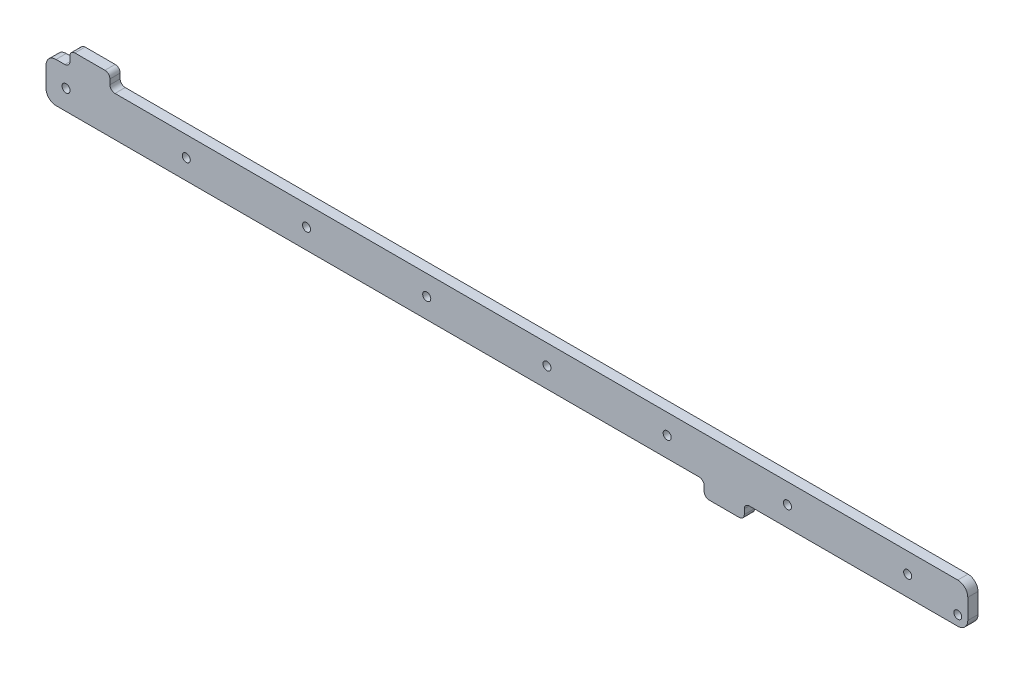
SolidWorks part; units mm, degrees
material "PC High Viscosity"
ref_plane "Front Plane" through (0, 0, 0) normal (0, 0, 1) x (1, 0, 0)
ref_plane "Top Plane" through (0, 0, 0) normal (0, 1, 0) x (1, 0, 0)
ref_plane "Right Plane" through (0, 0, 0) normal (1, 0, 0) x (0, 0, -1)
sketch "Sketch1" plane through (0, 0, 0) normal (0, 0, 1) x (1, 0, 0)
  line L1 (0, 0) -> (40.5308, 0)
  line L2 (0, 0) -> (0, 25.4)
  line L3 (0, 25.4) -> (15.1308, 25.4)
  line L4 (584.2, 0) -> (584.2, 25.4)
  line L5 (15.1308, 34.925) -> (40.5308, 34.925)
  line L6 (40.5308, 34.925) -> (40.5308, 25.4)
  line L7 (15.1308, 34.925) -> (15.1308, 25.4)
  line L11 (584.2, 10.0162) -> (577.85, 13.6823) construction
  line L12 (577.85, 13.6823) -> (571.5, 10.0162) construction
  line L13 (571.5, 10.0162) -> (571.5, 2.6838) construction
  line L14 (571.5, 2.6838) -> (577.85, -0.9823) construction
  line L15 (577.85, -0.9823) -> (584.2, 2.6838) construction
  line L16 (584.2, 2.6838) -> (584.2, 10.0162) construction
  line L19 (417.1409, 0) -> (417.1409, -9.525)
  line L20 (417.1409, -9.525) -> (442.5409, -9.525)
  line L21 (442.5409, -9.525) -> (442.5409, 0)
  line L22 (40.5308, 25.4) -> (584.2, 25.4)
  line L23 (40.5308, 0) -> (417.1409, 0)
  line L24 (442.5409, 0) -> (584.2, 0)
  circle A0 centre (577.85, 6.35) radius 2.4892
  circle A1 centre (577.85, 6.35) radius 6.35 construction
  point P24 (417.1409, -4.7625)
  dimension "D5" = 4.9784
  dimension "D6" = 9.525
  dimension "D7" = 12.7
  dimension "D1" = 584.2
  dimension "D2" = 25.4
  dimension "D3" = 25.4
  dimension "D4" = 167.0591
  dimension "D8" = 40.5308
  dimension "D9" = 25.4
extrude "Boss-Extrude1" add sketch "Sketch1" along normal blind 6.477
fillet "Fillet2" radius 6.35 4 edges at (0, 0, 3.2385) (0, 25.4, 3.2385) (584.2, 25.4, 3.2385) (584.2, 0, 3.2385)
sketch "Sketch2" plane through (0, 0, 6.477) normal (0, 0, 1) x (1, 0, 0)
  line L0 (6.35, 25.4) -> (15.1308, 25.4) construction
  line L1 (584.2, 19.05) -> (584.2, 6.35) construction
  circle A0 centre (546.1, 12.7) radius 2.0193
  dimension "D1" = 4.0386
  dimension "D2" = 12.7
  dimension "D3" = 38.1
hole_wizard "CSK for #10 Flat Head Machine Screw (100)1" positions "Sketch4" profile "Sketch5" countersink size "#10" standard "ANSI Inch" end condition through all
sketch "Sketch4" plane through (0, 0, 6.477) normal (0, 0, 1) x (1, 0, 0)
  line L0 (584.2, 12.7) -> (0, 12.7) construction
  line L1 (584.2, 19.05) -> (584.2, 6.35) construction
  line L2 (0, 6.35) -> (0, 19.05) construction
  line L3 (6.35, 25.4) -> (15.1308, 25.4) construction
  point P11 (546.1, 12.7)
  dimension "D1" = 12.7
  dimension "D2" = 38.1
sketch "Sketch5" plane through (546.1, 12.7, 6.477) normal (1, 0, 0) x (0, -1, 0)
  line L0 (0, 0) -> (0, 6.477)
  line L1 (0, 6.477) -> (2.5527, 6.477)
  line L2 (2.5527, 6.477) -> (2.5527, 1.9608)
  line L3 (2.5527, 1.9608) -> (4.8895, 0)
  line L5 (4.8895, 0) -> (0, 0)
  line L6 (-2.5527, 1.9608) -> (-4.8895, 0) construction
  line L11 (0, -6.35) -> (0, 107.95) construction
  dimension "Thru Hole Dia." = 5.1054
  dimension "Thru Hole Depth" = 6.477
  dimension "Near C'Sink Dia." = 9.779
  dimension "Near C'Sink Angle" = 100
pattern_linear "LPattern1" count 8 spacing 76.2 along (-1, 0, 0) of "CSK for #10 Flat Head Machine Screw (100)1"
mirror "Mirror2" about plane through (0, 0, 0) normal (0, 0, 1) of bodies 108
delete or keep bodies "Body-Delete/Keep 1" type delete bodies bodies 108
fillet "Fillet3" radius 3.175 8 edges at (442.5409, 0, -3.2385) (442.5409, -9.525, -3.2385) (417.1409, -9.525, -3.2385) (417.1409, 0, -3.2385) (40.5308, 25.4, -3.2385) (40.5308, 34.925, -3.2385) (15.1308, 34.925, -3.2385) (15.1308, 25.4, -3.2385)
